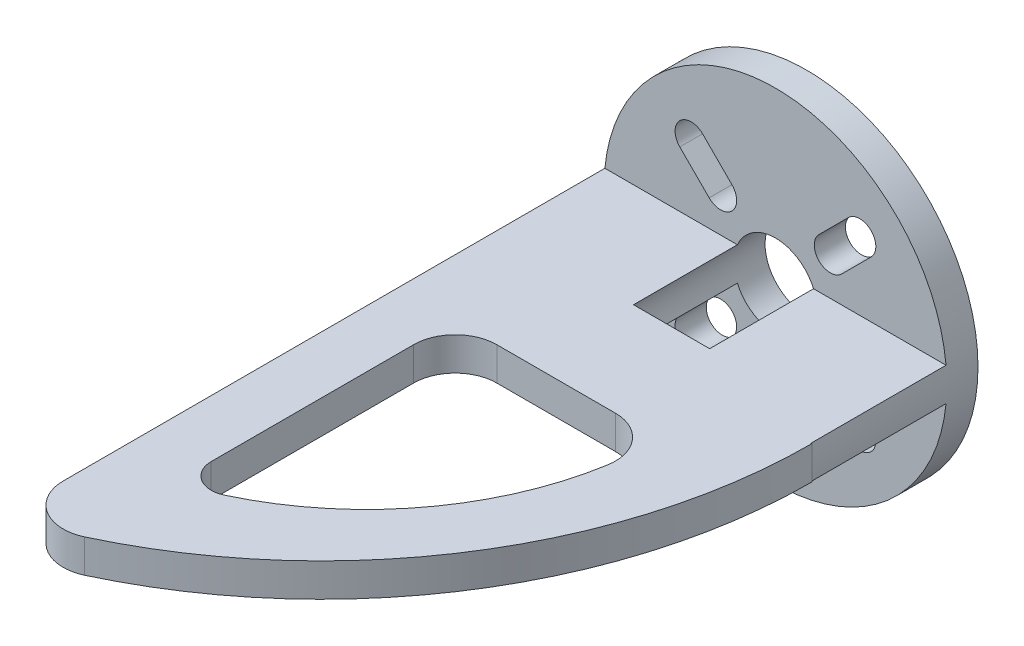
SolidWorks part; units mm, degrees
ref_plane "前视基准面" through (0, 0, 0) normal (0, 0, 1) x (1, 0, 0)
ref_plane "上视基准面" through (0, 0, 0) normal (0, 1, 0) x (1, 0, 0)
ref_plane "右视基准面" through (0, 0, 0) normal (1, 0, 0) x (0, 0, -1)
other "Configuration Table"
sketch "草图1" plane through (0, 0, 0) normal (0, 0, 1) x (1, 0, 0)
  line L6 (-8.1135, 8.0793) -> (-5.2851, 5.2509) construction
  line L7 (-7.0175, 9.1753) -> (-4.1891, 6.3469)
  line L8 (-9.2095, 6.9833) -> (-6.3811, 4.1548)
  line L15 (8.1135, 8.1135) -> (5.2851, 5.2851) construction
  line L16 (7.0175, 9.2095) -> (4.1891, 6.3811)
  line L17 (9.2095, 7.0175) -> (6.3811, 4.1891)
  line L18 (-8.1135, -8.1135) -> (-5.2851, -5.2851) construction
  line L19 (-7.0175, -9.2095) -> (-4.1891, -6.3811)
  line L20 (-9.2095, -7.0175) -> (-6.3811, -4.1891)
  line L21 (8.1135, -8.1135) -> (5.2851, -5.2851) construction
  line L22 (7.0175, -9.2095) -> (4.1891, -6.3811)
  line L23 (9.2095, -7.0175) -> (6.3811, -4.1891)
  line L24 (0, 0) -> (-11.6673, 11.6673) construction
  line L25 (18.15, 0) -> (-18.15, 0) construction
  line L26 (0, 0) -> (-11.6673, -11.6673) construction
  circle A0 centre (0, 0) radius 4
  arc A5 (-7.0175, 9.1753) -> (-9.2095, 6.9833) centre (-8.1135, 8.0793) ccw
  arc A6 (-6.3811, 4.1548) -> (-4.1891, 6.3469) centre (-5.2851, 5.2509) ccw
  arc A11 (7.0175, 9.2095) -> (9.2095, 7.0175) centre (8.1135, 8.1135) cw
  arc A12 (6.3811, 4.1891) -> (4.1891, 6.3811) centre (5.2851, 5.2851) cw
  arc A13 (-7.0175, -9.2095) -> (-9.2095, -7.0175) centre (-8.1135, -8.1135) cw
  arc A14 (-6.3811, -4.1891) -> (-4.1891, -6.3811) centre (-5.2851, -5.2851) cw
  arc A15 (7.0175, -9.2095) -> (9.2095, -7.0175) centre (8.1135, -8.1135) ccw
  arc A16 (6.3811, -4.1891) -> (4.1891, -6.3811) centre (5.2851, -5.2851) ccw
  circle A17 centre (0, 0) radius 16.5
  point P20 (-6.6993, 6.6651)
  point P39 (6.6993, 6.6993)
  point P46 (-6.6993, -6.6993)
  point P53 (6.6993, -6.6993)
extrude "凸台-拉伸4" add sketch "草图1" along normal blind 3
sketch "草图3" plane through (0, 0, 3) normal (0, 0, 1) x (1, 0, 0)
  line L0 (-16.5, 0) -> (16.5, 0) construction
  line L1 (0, -1.65) -> (0, 1.65) construction
  line L2 (16.4222, 1.6) -> (3.6661, 1.6)
  line L3 (-16.4222, 1.6) -> (-3.6661, 1.6)
  line L4 (-16.4222, -1.6) -> (-3.6661, -1.6)
  line L5 (16.4222, -1.6) -> (3.6661, -1.6)
  line L6 (0, 0) -> (5.9875, 5.9875) construction
  circle A0 centre (0, 0) radius 16.5 construction
  arc A2 (-3.6661, 1.6) -> (-3.6661, -1.6) centre (0, 0) ccw
  circle A3 centre (0, 0) radius 4 construction
  arc A4 (-16.4222, 1.6) -> (-16.4222, -1.6) centre (0, 0) ccw
  arc A5 (16.4222, 1.6) -> (16.4222, -1.6) centre (0, 0) cw
  arc A6 (3.6661, 1.6) -> (3.6661, -1.6) centre (0, 0) cw
  point P7 (0, 0)
  point P11 (-11.003, 1.6)
extrude "凸台-拉伸6" add sketch "草图3" along normal blind 10
sketch "草图4" plane through (0, 0, 13) normal (0, 0, 1) x (1, 0, 0)
  line L0 (0, 0) -> (20.4119, 0) construction
  line L1 (0, -8.25) -> (0, 8.25) construction
  line L2 (-16.4222, 1.6) -> (16.4222, 1.6)
  line L3 (16.4222, -1.6) -> (-16.4222, -1.6)
  arc A0 (16.4222, 1.6) -> (16.4222, -1.6) centre (0, 0) cw
  arc A1 (-16.4222, 1.6) -> (-16.4222, -1.6) centre (0, 0) ccw
extrude "凸台-拉伸12" add sketch "草图4" along normal blind 3 contours L3 A1 L2 A0
sketch "草图8" plane through (0, 1.6, 0) normal (0, 1, 0) x (1, 0, 0)
  line L0 (-16.4222, -16) -> (-16.4222, -55.1527)
  line L1 (-16.4222, -16) -> (16.5, -16)
  line L2 (-6.9193, -22.9106) -> (4.5029, -22.9106)
  line L3 (-10.9193, -26.9106) -> (-10.9193, -46.4022)
  arc A0 (16.5, -16) -> (-10.729, -58.7766) centre (-30.7154, -16) cw
  arc A1 (-16.4222, -55.1527) -> (-10.729, -58.7766) centre (-12.4222, -55.1527) ccw
  arc A2 (-10.9193, -46.4022) -> (-7.5034, -48.5766) centre (-8.5193, -46.4022) ccw
  arc A3 (8.4485, -27.5682) -> (-7.5034, -48.5766) centre (-19.4952, -22.9106) cw
  arc A4 (-6.9193, -22.9106) -> (-10.9193, -26.9106) centre (-6.9193, -26.9106) ccw
  arc A5 (4.5029, -22.9106) -> (8.4485, -27.5682) centre (4.5029, -26.9106) cw
  point P14 (0, 0)
  dimension "D1" = 4
  dimension "D2" = 4
  dimension "D3" = 4
extrude "凸台-拉伸14" add sketch "草图8" against normal blind 3.2
